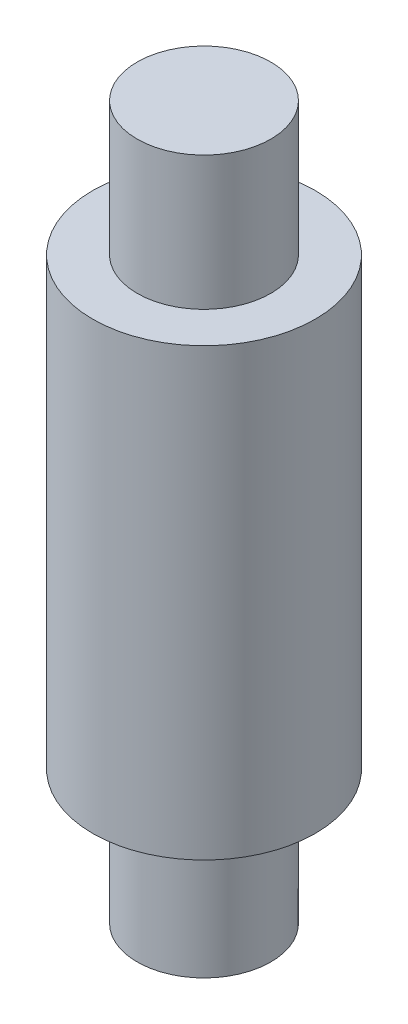
SolidWorks part; units mm, degrees
ref_plane "前视基准面" through (0, 0, 0) normal (0, 0, 1) x (1, 0, 0)
ref_plane "上视基准面" through (0, 0, 0) normal (0, 1, 0) x (1, 0, 0)
ref_plane "右视基准面" through (0, 0, 0) normal (1, 0, 0) x (0, 0, -1)
other "Configuration Table"
sketch "草图1" plane through (0, 0, 0) normal (0, 1, 0) x (1, 0, 0)
  circle A0 centre (0, 0) radius 2.5
  dimension "D1" = 5
extrude "凸台-拉伸2" add sketch "草图1" against normal mid plane 10
sketch "草图2" plane through (0, 5, 0) normal (0, 1, 0) x (1, 0, 0)
  circle A0 centre (0, 0) radius 1.5
  dimension "D1" = 3
extrude "凸台-拉伸3" add sketch "草图2" along normal blind 3
sketch "草图3" plane through (0, -5, 0) normal (0, -1, 0) x (1, 0, 0)
  circle A0 centre (0, 0) radius 1.5
  dimension "D1" = 3
extrude "凸台-拉伸4" add sketch "草图3" along normal blind 3
